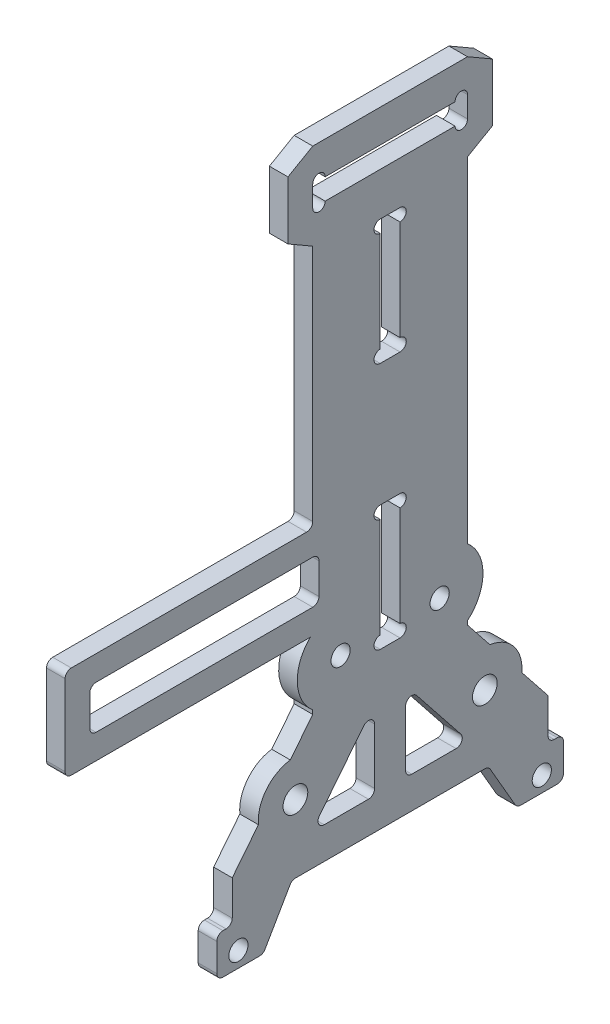
SolidWorks part; units mm, degrees
material "Thornel Mat VMA"
ref_plane "前视基准面" through (0, 0, 0) normal (0, 0, 1) x (1, 0, 0)
ref_plane "上视基准面" through (0, 0, 0) normal (0, 1, 0) x (1, 0, 0)
ref_plane "右视基准面" through (0, 0, 0) normal (1, 0, 0) x (0, 0, -1)
sketch "草图1" plane through (0, 0, 0) normal (1, 0, 0) x (0, 0, -1)
  line L0 (0, 0) -> (0, 14) construction
  line L1 (12.5, -39.75) -> (-12.5, -39.75) construction
  line L2 (12.5, -39.75) -> (12.5, 39.75) construction
  line L3 (12.5, 39.75) -> (-12.5, 39.75)
  line L4 (-12.5, -39.75) -> (-12.5, 39.75) construction
  line L5 (12.5, -39.75) -> (-12.5, 39.75) construction
  line L6 (12.5, 39.75) -> (-12.5, -39.75) construction
  line L7 (-12.5, 39.75) -> (-16.5, 37.4406)
  line L8 (1.6, 3.9) -> (-1.6, 3.9)
  line L9 (1.6, 3.9) -> (1.6, 24.1)
  line L10 (1.6, 24.1) -> (-1.6, 24.1)
  line L11 (-1.6, 3.9) -> (-1.6, 24.1)
  line L12 (1.6, 3.9) -> (-1.6, 24.1) construction
  line L13 (1.6, 24.1) -> (-1.6, 3.9) construction
  line L14 (1.6, -36.1) -> (-1.6, -36.1)
  line L15 (1.6, -36.1) -> (1.6, -15.9)
  line L16 (1.6, -15.9) -> (-1.6, -15.9)
  line L17 (-1.6, -36.1) -> (-1.6, -15.9)
  line L18 (1.6, -36.1) -> (-1.6, -15.9) construction
  line L19 (1.6, -15.9) -> (-1.6, -36.1) construction
  line L20 (12.5, 31.05) -> (-12.5, 31.05)
  line L21 (12.5, 31.05) -> (12.5, 34.45)
  line L22 (12.5, 34.45) -> (-12.5, 34.45)
  line L23 (-12.5, 31.05) -> (-12.5, 34.45)
  line L24 (12.5, 31.05) -> (-12.5, 34.45) construction
  line L25 (12.5, 34.45) -> (-12.5, 31.05) construction
  line L26 (-16.5, 37.4406) -> (-16.5, 28.0594)
  line L27 (-16.5, 28.0594) -> (-12.5, 25.75)
  line L28 (-12.5, 25.75) -> (-12.5, -13.75)
  line L29 (12.5, 39.75) -> (16.5, 37.4406)
  line L30 (16.5, 37.4406) -> (16.5, 28.0594)
  line L31 (16.5, 28.0594) -> (12.5, 25.75)
  line L32 (12.5, 25.75) -> (12.5, -13.75)
  line L33 (-16.5, 32.75) -> (0, 32.75) construction
  line L34 (5.6, 27.05) -> (9.5, 27.05) construction
  line L35 (-5.6, -28.75) -> (-9.5, -28.75) construction
  line L36 (-5.6, -28.75) -> (-5.6, -2.85) construction
  line L37 (-5.6, 27.05) -> (-9.5, 27.05) construction
  line L38 (-9.5, -28.75) -> (-9.5, -2.85) construction
  line L39 (-5.6, -28.75) -> (-9.5, 27.05) construction
  line L40 (-5.6, 27.05) -> (-9.5, -28.75) construction
  line L41 (5.6, -28.75) -> (9.5, -28.75) construction
  line L42 (5.6, -28.75) -> (5.6, -2.85) construction
  line L43 (9.5, -28.75) -> (9.5, -2.85) construction
  line L44 (-9.5, 1.15) -> (-5.6, 1.15) construction
  line L45 (-9.5, -2.85) -> (-5.6, -2.85) construction
  line L46 (-7.55, -0.85) -> (-3.3992, -0.85) construction
  line L47 (9.5, -2.85) -> (5.6, -2.85) construction
  line L48 (9.5, 1.15) -> (5.6, 1.15) construction
  line L49 (-9.5, 1.15) -> (-9.5, 27.05) construction
  line L50 (-5.6, 1.15) -> (-5.6, 27.05) construction
  line L51 (5.6, 1.15) -> (5.6, 27.05) construction
  line L52 (9.5, 1.15) -> (9.5, 27.05) construction
  line L53 (12.5, -13.75) -> (52.5, -13.75) construction
  line L54 (52.5, -13.75) -> (52.5, -28.75) construction
  line L55 (12.5, -28.75) -> (12.5, -39.75)
  line L56 (12.5, -28.75) -> (52.5, -28.75) construction
  line L57 (12.5, -39.75) -> (28, -59.25)
  line L58 (11.5, -17.75) -> (48.5, -17.75) construction
  line L59 (11.5, -17.75) -> (11.5, -24.75) construction
  line L60 (11.5, -24.75) -> (48.5, -24.75) construction
  line L61 (48.5, -17.75) -> (48.5, -24.75) construction
  line L62 (11.5, -17.75) -> (48.5, -24.75) construction
  line L63 (11.5, -24.75) -> (48.5, -17.75) construction
  line L64 (28, -59.25) -> (28, -69.25)
  line L65 (28, -69.25) -> (20.5, -69.25)
  line L66 (15.8812, -61.25) -> (20.5, -69.25)
  line L67 (15.8812, -61.25) -> (-15.8812, -61.25)
  line L68 (-12.5, -39.75) -> (-28, -59.25)
  line L69 (-28, -59.25) -> (-28, -69.25)
  line L70 (-28, -69.25) -> (-20.5, -69.25)
  line L71 (-15.8812, -61.25) -> (-20.5, -69.25)
  line L73 (19.2282, -56.25) -> (-19.2282, -56.25) construction
  line L89 (12.5, -13.75) -> (12.5, -28.75) construction
  line L90 (-12.5, -13.75) -> (-52.5, -13.75)
  line L91 (-52.5, -13.75) -> (-52.5, -28.75)
  line L92 (-12.5, -28.75) -> (-52.5, -28.75)
  line L93 (-11.5, -24.75) -> (-48.5, -24.75)
  line L94 (-48.5, -17.75) -> (-48.5, -24.75)
  line L95 (-11.5, -17.75) -> (-48.5, -17.75)
  line L96 (-11.5, -17.75) -> (-11.5, -24.75)
  line L97 (-12.5, -28.75) -> (-12.5, -39.75)
  line L98 (12.5, -28.75) -> (12.5, -13.75)
  circle A0 centre (-8, -33.75) radius 1.55
  circle A1 centre (8, -33.75) radius 1.55
  circle A2 centre (1.6, 4.905) radius 1.005
  circle A3 centre (1.6, 23.095) radius 1.005
  circle A4 centre (-1.6, 23.095) radius 1.005
  circle A5 centre (-1.6, 4.905) radius 1.005
  circle A6 centre (1.6, -16.905) radius 1.005
  circle A7 centre (-1.6, -16.905) radius 1.005
  circle A8 centre (-1.6, -35.095) radius 1.005
  circle A9 centre (1.6, -35.095) radius 1.005
  circle A10 centre (-11.495, 34.45) radius 1.005
  circle A11 centre (-11.495, 31.05) radius 1.005
  circle A12 centre (11.495, 34.45) radius 1.005
  circle A13 centre (11.495, 31.05) radius 1.005
  circle A14 centre (24.5, -66.75) radius 1.55
  circle A15 centre (-24.5, -66.75) radius 1.55
  point P0 (0, 0)
  point P12 (0, 14)
  point P17 (0, -26)
  point P38 (0, 32.75)
  point P59 (-7.55, -0.85)
  point P80 (30, -21.25)
  dimension "D2" = 3.1
  dimension "D10" = 2.01
  dimension "D1" = 25
  dimension "D3" = 6
  dimension "D4" = 16
  dimension "D5" = 66.5
  dimension "D6" = 14
  dimension "D7" = 40
  dimension "D8" = 20.2
  dimension "D9" = 3.2
  dimension "D11" = 25
  dimension "D12" = 60
  dimension "D13" = 4
  dimension "D14" = 7
  dimension "D15" = 4
  dimension "D16" = 3
  dimension "D17" = 4
  dimension "D18" = 5
  dimension "D19" = 4
  dimension "D20" = 40
  dimension "D21" = 5
  dimension "D22" = 15
  dimension "D23" = 4
  dimension "D24" = 4
  dimension "D25" = 4
  dimension "D26" = 2
  dimension "D27" = 3.4
  dimension "D28" = 49
  dimension "D29" = 33
  dimension "D30" = 2.5
  dimension "D31" = 3.5
  dimension "D32" = 4
  dimension "D33" = 120
  dimension "D34" = 8
  dimension "D35" = 10
  dimension "D37" = 5
extrude "凸台-拉伸1" add sketch "草图1" along normal blind 3
sketch "草图2" plane through (3, 0, 0) normal (1, 0, 0) x (0, 0, -1)
  line L0 (0, -61.25) -> (0, -50.25) construction
  line L1 (33.5, -57.75) -> (25.5, -57.75) construction
  line L2 (33.5, -57.75) -> (33.5, -62.75)
  line L3 (33.5, -62.75) -> (25.5, -62.75)
  line L4 (25.5, -57.75) -> (25.5, -62.75)
  line L5 (33.5, -57.75) -> (25.5, -62.75) construction
  line L6 (33.5, -62.75) -> (25.5, -57.75) construction
  line L7 (15.8812, -61.25) -> (-15.8812, -61.25) construction
  line L8 (-33.5, -62.75) -> (-25.5, -62.75)
  line L9 (-25.5, -57.75) -> (-25.5, -62.75)
  line L10 (-33.5, -57.75) -> (-25.5, -57.75) construction
  line L11 (-33.5, -57.75) -> (-33.5, -62.75)
  line L12 (25.5, -57.75) -> (25.5, -56.1048)
  line L13 (12.5, -39.75) -> (28, -59.25) construction
  line L14 (25.5, -56.1048) -> (33.5, -56.1048)
  line L15 (33.5, -56.1048) -> (33.5, -57.75)
  line L16 (-25.5, -57.75) -> (-25.5, -56.1048)
  line L17 (-33.5, -56.1048) -> (-33.5, -57.75)
  line L18 (-25.5, -56.1048) -> (-33.5, -56.1048)
  line L19 (15.3, -50.25) -> (-15.3, -50.25) construction
  line L20 (12.7257, -56.1048) -> (2.5, -56.1048)
  line L21 (2.5, -56.1048) -> (2.5, -43.2402)
  line L23 (2.5, -43.2402) -> (12.7257, -56.1048)
  line L25 (-2.5, -56.1048) -> (-2.5, -43.2402)
  line L26 (-12.7257, -56.1048) -> (-2.5, -56.1048)
  line L27 (-2.5, -43.2402) -> (-12.7257, -56.1048)
  line L28 (12.5, -39.75) -> (28, -59.25) construction
  circle A0 centre (24.5, -66.75) radius 1.55 construction
  circle A1 centre (15.3, -50.25) radius 2
  circle A2 centre (-15.3, -50.25) radius 2
  circle A3 centre (-24.5, -66.75) radius 1.55 construction
  point P0 (29.5, -60.25)
  dimension "D5" = 4
  dimension "D1" = 6.5
  dimension "D2" = 5
  dimension "D3" = 8
  dimension "D4" = 1
  dimension "D6" = 30.6
  dimension "D7" = 16.5
  dimension "D8" = 5
  dimension "D9" = 10
extrude "切除-拉伸1" cut sketch "草图2" against normal blind 10
sketch "草图3" plane through (3, 0, 0) normal (1, 0, 0) x (0, 0, -1)
  line L0 (-3.7574, -27.75) -> (-11.6056, -27.75)
  line L1 (11.6056, -27.75) -> (3.7574, -27.75)
  line L2 (3.7574, -27.75) -> (3.7574, -39.3178)
  line L3 (-3.7574, -27.75) -> (-3.7574, -39.3178)
  line L4 (-21.2756, -50.7903) -> (-16.1219, -44.3066)
  line L6 (0, 0) -> (0, -22.5255) construction
  line L7 (-12.5, -39.75) -> (-25.5, -56.1048) construction
  line L8 (21.2756, -50.7903) -> (16.1219, -44.3066)
  circle A0 centre (-8, -33.75) radius 1.55 construction
  circle A1 centre (8, -33.75) radius 1.55 construction
  circle A2 centre (-8, -33.75) radius 1.55
  circle A3 centre (8, -33.75) radius 1.55
  arc A4 (3.7574, -39.3178) -> (11.6056, -27.75) centre (8, -33.75) ccw
  arc A5 (-11.6056, -27.75) -> (-3.7574, -39.3178) centre (-8, -33.75) ccw
  arc A7 (-16.1219, -44.3066) -> (-21.2756, -50.7903) centre (-15.3, -50.25) ccw
  arc A8 (16.1219, -44.3066) -> (21.2756, -50.7903) centre (15.3, -50.25) cw
  dimension "D1" = 14
  dimension "D5" = 12
  dimension "D2" = 6
  dimension "D3" = 4.2426
  dimension "D4" = 4.2426
extrude "凸台-拉伸2" add sketch "草图3" against normal up to surface (3 mm away) up to face at (0, -51.8166, 5.9086)
fillet "圆角1" radius 1 23 edges at (1.5, -62.75, 25.5) (1.5, -62.75, 28) (1.5, -69.25, 28) (1.5, -69.25, 20.5) (1.5, -61.25, 15.8812) (1.5, -61.25, -15.8812) (1.5, -69.25, -20.5) (1.5, -69.25, -28) (1.5, -62.75, -25.5) (1.5, -62.75, -28) (1.5, -56.1048, 12.7257) (1.5, -43.2402, 2.5) (1.5, -56.1048, 2.5) (1.5, -56.1048, -2.5) (1.5, -43.2402, -2.5) (1.5, -56.1048, -12.7257) (1.5, -24.75, 48.5) (1.5, -17.75, 48.5) (1.5, -13.75, 52.5) (1.5, -28.75, 52.5) (1.5, -17.75, 11.5) (1.5, -24.75, 11.5) (1.5, -13.75, 12.5)
